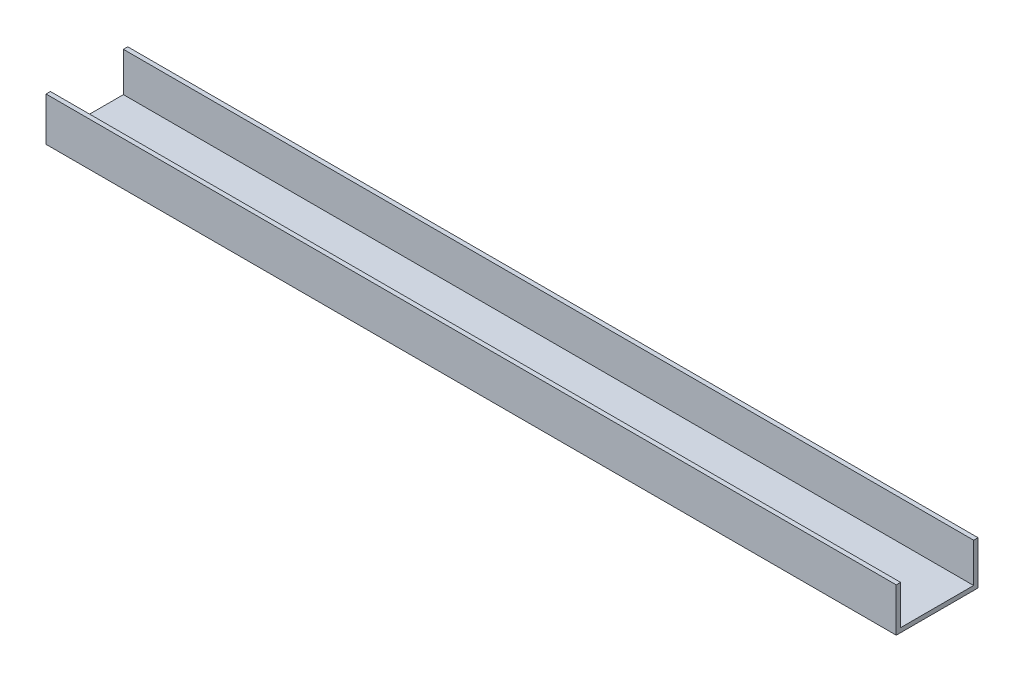
SolidWorks part; units mm, degrees
ref_plane "정면" through (0, 0, 0) normal (0, 0, 1) x (1, 0, 0)
ref_plane "윗면" through (0, 0, 0) normal (0, 1, 0) x (1, 0, 0)
ref_plane "우측면" through (0, 0, 0) normal (1, 0, 0) x (0, 0, -1)
sketch "스케치1" plane through (0, 0, 0) normal (0, 1, 0) x (1, 0, 0)
  line L1 (0, 0) -> (780, 0)
  line L2 (0, 0) -> (0, 75)
  line L3 (0, 75) -> (780, 75)
  line L4 (780, 0) -> (780, 75)
  dimension "D1" = 780
  dimension "D2" = 75
extrude "보스-돌출1" add sketch "스케치1" along normal blind 4
sketch "스케치2" plane through (0, 4, 0) normal (0, 1, 0) x (1, 0, 0)
  line L0 (780, 0) -> (780, 75) construction
  line L1 (0, 0) -> (780, 0)
  line L2 (0, 0) -> (0, 4)
  line L3 (0, 4) -> (780, 4)
  line L4 (780, 0) -> (780, 4)
  line L5 (0, 75) -> (0, 0) construction
  line L6 (780, 75) -> (0, 75)
  line L7 (780, 75) -> (780, 71)
  line L8 (780, 71) -> (0, 71)
  line L9 (0, 75) -> (0, 71)
  dimension "D1" = 4
  dimension "D2" = 4
extrude "보스-돌출2" add sketch "스케치2" along normal blind 36
